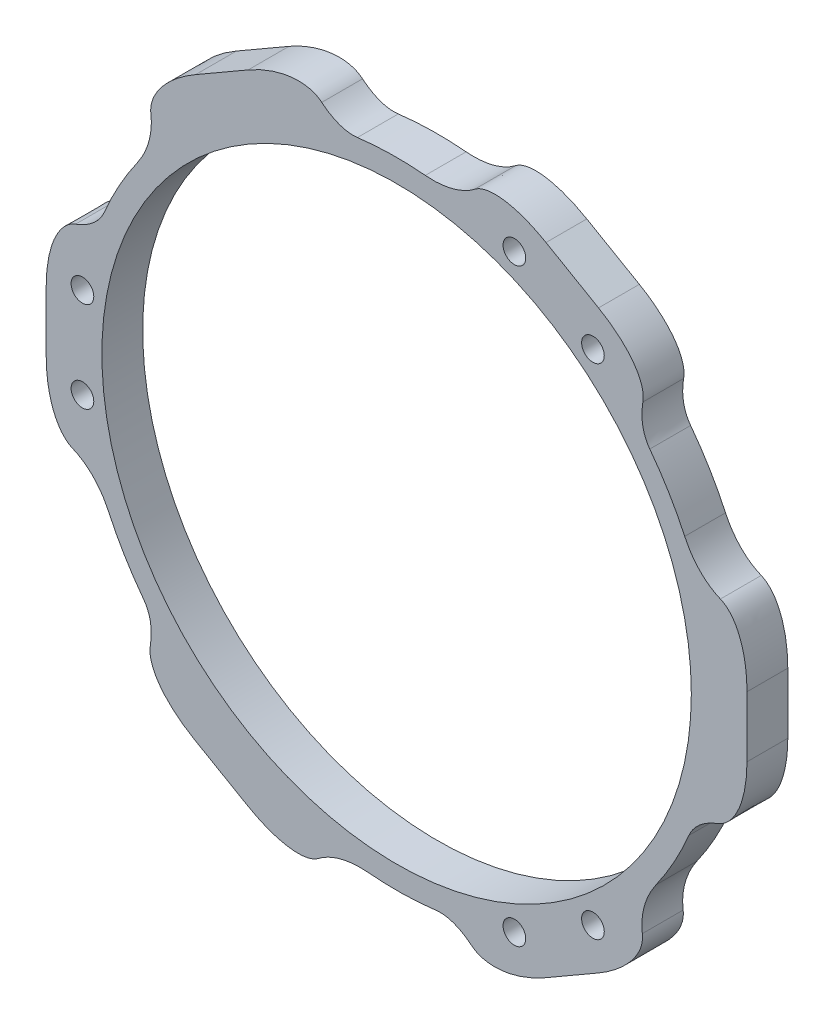
SolidWorks part; units mm, degrees
ref_plane "Front Plane" through (0, 0, 0) normal (0, 0, 1) x (1, 0, 0)
ref_plane "Top Plane" through (0, 0, 0) normal (0, 1, 0) x (1, 0, 0)
ref_plane "Right Plane" through (0, 0, 0) normal (1, 0, 0) x (0, 0, -1)
sketch "Sketch1" plane through (0, 0, 0) normal (0, 0, 1) x (1, 0, 0)
  line L6 (-16.3681, 35.1641) -> (-22.1631, 31.8183)
  line L7 (-38.637, 3.4069) -> (-38.637, -3.2847)
  line L8 (-20.8216, -32.5928) -> (-16.4739, -35.103)
  line L9 (16.3681, -35.1641) -> (22.1631, -31.8183)
  line L10 (38.637, -3.4069) -> (38.637, 3.2847)
  line L11 (22.269, 31.7572) -> (16.4739, 35.103)
  line L12 (-16.3681, 35.1641) -> (-22.1631, 31.8183)
  line L13 (-38.637, 3.4069) -> (-38.637, -3.2847)
  line L15 (16.3681, -35.1641) -> (22.1631, -31.8183)
  line L16 (38.637, -3.4069) -> (38.637, 3.2847)
  line L17 (22.269, 31.7572) -> (16.4739, 35.103)
  line L27 (-16.4739, -35.103) -> (-22.269, -31.7572) construction
  line L28 (-16.4739, -35.103) -> (-22.269, -31.7572)
  line L35 (-27.0644, -24.4754) -> (-24.4721, -21.3861)
  line L37 (-16.8117, -27.814) -> (-20.8216, -32.5928)
  circle A0 centre (-34.641, -5) radius 1.25 construction
  circle A1 centre (-34.641, 5) radius 1.25 construction
  circle A2 centre (12.9904, 32.5) radius 1.25 construction
  circle A3 centre (21.6506, 27.5) radius 1.25 construction
  circle A4 centre (21.6506, -27.5) radius 1.25 construction
  circle A5 centre (12.9904, -32.5) radius 1.25 construction
  arc A6 (-28.6051, 20.1681) -> (-32.2382, 13.6271) centre (0, 0) ccw
  arc A7 (-31.7686, -14.6887) -> (-27.9205, -21.1055) centre (0, 0) ccw
  arc A8 (-3.1635, -34.8567) -> (4.3177, -34.7327) centre (0, 0) ccw
  arc A9 (28.6051, -20.1681) -> (32.2382, -13.6271) centre (0, 0) ccw
  arc A10 (31.7686, 14.6887) -> (27.9205, 21.1055) centre (0, 0) ccw
  arc A11 (3.1635, 34.8567) -> (-4.3177, 34.7327) centre (0, 0) ccw
  arc A12 (-28.6051, 20.1681) -> (-32.2382, 13.6271) centre (0, 0) ccw
  arc A13 (-31.7686, -14.6887) -> (-27.9205, -21.1055) centre (0, 0) ccw
  arc A14 (-3.1635, -34.8567) -> (4.3177, -34.7327) centre (0, 0) ccw
  arc A15 (28.6051, -20.1681) -> (32.2382, -13.6271) centre (0, 0) ccw
  arc A16 (31.7686, 14.6887) -> (27.9205, 21.1055) centre (0, 0) ccw
  arc A17 (3.1635, 34.8567) -> (-4.3177, 34.7327) centre (0, 0) ccw
  circle A18 centre (-34.641, -5) radius 1.25
  circle A19 centre (-34.641, 5) radius 1.25
  circle A20 centre (12.9904, 32.5) radius 1.25
  circle A21 centre (21.6506, 27.5) radius 1.25
  circle A22 centre (21.6506, -27.5) radius 1.25
  circle A23 centre (12.9904, -32.5) radius 1.25
  circle A31 centre (0, 0) radius 32.5
  arc A51 (-16.8117, -27.814) -> (-24.4721, -21.3861) centre (0, 0) ccw
  arc A52 (-16.8117, -27.814) -> (-24.4721, -21.3861) centre (0, 0) ccw construction
  spline S24 degree 2 poles (20018.0304, -6218.9304) (192.3658, 262.0734) (-25.4386, 29.292) (-26.2323, 28.4437) (-26.6615, 27.603) (-123.8009, -162.6744) (20488.8575, 4480.5029) knots -83.757765 -83.757765 -83.757765 0.5 0.5 0.75 0.75 44.47631 44.47631 44.47631 only from (-22.1631, 31.8183) to (-27.0953, 25.5852)
  spline S25 degree 2 poles (-20068.3462, -6225.9324) (-4.2818, 286.6928) (-27.07, 24.2022) (-27.162, 23.1427) (-27.5729, 22.0839) (-136.5452, -258.6621) (-19878.5198, 6847.5241) knots -56.599758 -56.599758 -56.599758 0.5 0.5 0.75 0.75 70.569418 70.569418 70.569418 only from (-27.0953, 25.5852) to (-28.6051, 20.1681)
  spline S26 degree 2 poles (-19304.6139, 8338.2187) (134.0795, 161.3494) (-33.3539, 12.1077) (-34.0252, 11.5093) (-34.9497, 11.0979) (-285.6142, -100.4617) (-13434.0765, 16171.4862) knots -54.854338 -54.854338 -54.854338 0.25 0.25 0.5 0.5 76.100885 76.100885 76.100885 only from (-32.2382, 13.6271) to (-35.408, 10.9116)
  spline S27 degree 2 poles (6375.7637, -19980.6764) (89.3915, 185.5734) (-37.0555, 9.5638) (-37.6258, 8.77) (-38.0064, 7.642) (-38.3307, 6.6806) (-38.491, 5.5483) (-90.1333, -359.2843) (18121.9616, -10520.9097) knots -43.471704 -43.471704 -43.471704 0.25 0.25 0.5 0.5 0.75 0.75 89.168933 89.168933 89.168933 only from (-35.408, 10.9116) to (-38.637, 3.4069)
  spline S28 degree 2 poles (15394.7669, 14226.6576) (-130.7794, 297.6304) (-38.0869, -7.3845) (-37.7491, -8.496) (-37.2357, -9.288) (78.9797, -188.5519) (6364.1994, 19984.1225) knots -83.757765 -83.757765 -83.757765 0.5 0.5 0.75 0.75 44.47631 44.47631 44.47631 only from (-38.637, -3.2847) to (-35.7051, -10.6726)
  spline S29 degree 2 poles (-4642.3575, -20492.6638) (-250.4242, 139.6382) (-34.4947, -11.3422) (-33.6232, -11.9516) (-32.9117, -12.8369) (155.7354, -247.5826) (-15869.3897, -13791.5411) knots -56.599758 -56.599758 -56.599758 0.5 0.5 0.75 0.75 70.569418 70.569418 70.569418 only from (-35.7051, -10.6726) to (-31.7686, -14.6887)
  spline S30 degree 2 poles (-869.2724, -561.5927) (-37.2473, 25.8119) (-27.1625, -22.8314) (-16.9987, -71.8561) (-900.9243, -510.6357) knots -11.954832 -11.954832 -11.954832 0.25 0.25 14.167884 14.167884 14.167884 only from (-27.9205, -21.1055) to (-27.0644, -24.4754)
  spline S31 degree 2 poles (-19740.8402, -3354.4279) (-55.5598, -291.2204) (-27.0871, -24.7299) (-26.9793, -23.7208) (-27.1613, -22.8376) (-71.3618, 191.6829) (-16081.7661, -11939.2208) knots -73.205513 -73.205513 -73.205513 0.5 0.5 0.75 0.75 54.368798 54.368798 54.368798 only from (-27.1537, -25.2085) to (-27.9205, -21.1055) construction
  spline S32 degree 2 poles (-4623.2634, 20445.5881) (-323.1452, 35.5569) (-12.6483, -36.6765) (-11.5168, -36.9397) (-10.5741, -36.891) (202.7806, -25.8775) (-14124.6581, 15503.6196) knots -83.757765 -83.757765 -83.757765 0.5 0.5 0.75 0.75 44.47631 44.47631 44.47631 only from (-16.4739, -35.103) to (-8.6098, -36.2578)
  spline S33 degree 2 poles (15425.9887, -14266.7314) (-246.1423, -147.0546) (-7.4247, -35.5444) (-6.4612, -35.0943) (-5.3387, -34.9208) (292.2805, 11.0795) (4009.1301, -20639.0652) knots -56.599758 -56.599758 -56.599758 0.5 0.5 0.75 0.75 70.569418 70.569418 70.569418 only from (-8.6098, -36.2578) to (-3.1635, -34.8567)
  spline S34 degree 2 poles (2431.1977, -20887.3954) (-206.7724, 35.4415) (6.1913, -34.9392) (7.0452, -35.2214) (7.8638, -35.8163) (229.8095, -197.1183) (-7287.8796, -19719.9947) knots -54.854338 -54.854338 -54.854338 0.25 0.25 0.5 0.5 76.100885 76.100885 76.100885 only from (4.3177, -34.7327) to (8.2543, -36.12)
  spline S35 degree 2 poles (14115.8916, 15511.9115) (-205.407, -15.3714) (10.2452, -36.8729) (11.2179, -36.9699) (12.3851, -36.7355) (13.3798, -36.5357) (14.4405, -36.1083) (356.216, 101.5844) (50.3943, 20954.5339) knots -43.471704 -43.471704 -43.471704 0.25 0.25 0.5 0.5 0.75 0.75 89.168933 89.168933 89.168933 only from (8.2543, -36.12) to (16.3681, -35.1641)
  spline S36 degree 2 poles (-20018.0304, 6218.9305) (-192.3658, -262.0734) (25.4386, -29.292) (26.2323, -28.4437) (26.6615, -27.603) (123.8009, 162.6744) (-20488.8575, -4480.5029) knots -83.757765 -83.757765 -83.757765 0.5 0.5 0.75 0.75 44.47631 44.47631 44.47631 only from (22.1631, -31.8183) to (27.0953, -25.5852)
  spline S37 degree 2 poles (20068.3462, 6225.9324) (4.2818, -286.6928) (27.07, -24.2022) (27.162, -23.1427) (27.5729, -22.0839) (136.5452, 258.6621) (19878.5198, -6847.5241) knots -56.599758 -56.599758 -56.599758 0.5 0.5 0.75 0.75 70.569418 70.569418 70.569418 only from (27.0953, -25.5852) to (28.6051, -20.1681)
  spline S38 degree 2 poles (19304.6139, -8338.2187) (-134.0795, -161.3494) (33.3539, -12.1077) (34.0252, -11.5093) (34.9497, -11.0979) (285.6142, 100.4617) (13434.0765, -16171.4862) knots -54.854338 -54.854338 -54.854338 0.25 0.25 0.5 0.5 76.100885 76.100885 76.100885 only from (32.2382, -13.6271) to (35.408, -10.9116)
  spline S39 degree 2 poles (-6375.7637, 19980.6764) (-89.3915, -185.5734) (37.0555, -9.5638) (37.6258, -8.77) (38.0064, -7.642) (38.3307, -6.6806) (38.491, -5.5483) (90.1333, 359.2843) (-18121.9616, 10520.9097) knots -43.471704 -43.471704 -43.471704 0.25 0.25 0.5 0.5 0.75 0.75 89.168933 89.168933 89.168933 only from (35.408, -10.9116) to (38.637, -3.4069)
  spline S40 degree 2 poles (-15394.7669, -14226.6576) (130.7794, -297.6304) (38.0869, 7.3845) (37.7491, 8.496) (37.2357, 9.288) (-78.9797, 188.5519) (-6364.1994, -19984.1225) knots -83.757765 -83.757765 -83.757765 0.5 0.5 0.75 0.75 44.47631 44.47631 44.47631 only from (38.637, 3.2847) to (35.7051, 10.6726)
  spline S41 degree 2 poles (4642.3575, 20492.6638) (250.4242, -139.6382) (34.4947, 11.3422) (33.6232, 11.9516) (32.9117, 12.8369) (-155.7354, 247.5826) (15869.3897, 13791.5411) knots -56.599758 -56.599758 -56.599758 0.5 0.5 0.75 0.75 70.569418 70.569418 70.569418 only from (35.7051, 10.6726) to (31.7686, 14.6887)
  spline S42 degree 2 poles (16873.4162, 12549.1767) (72.6929, -196.7909) (27.1625, 22.8314) (26.98, 23.712) (27.0859, 24.7184) (55.8047, 297.58) (20721.9561, 3548.5085) knots -54.854338 -54.854338 -54.854338 0.25 0.25 0.5 0.5 76.100885 76.100885 76.100885 only from (27.9205, 21.1055) to (27.1537, 25.2085)
  spline S43 degree 2 poles (-20491.6552, 4468.7649) (116.0155, -170.202) (26.8103, 27.3091) (26.4079, 28.1999) (25.6213, 29.0935) (24.951, 29.8551) (24.0505, 30.56) (-266.0827, 257.6999) (-18172.3559, -10433.6242) knots -43.471704 -43.471704 -43.471704 0.25 0.25 0.5 0.5 0.75 0.75 89.168933 89.168933 89.168933 only from (27.1537, 25.2085) to (22.269, 31.7572)
  spline S44 degree 2 poles (4623.2634, -20445.5881) (323.1452, -35.5569) (12.6483, 36.6765) (11.5168, 36.9397) (10.5741, 36.891) (-202.7806, 25.8775) (14124.6581, -15503.6196) knots -83.757765 -83.757765 -83.757765 0.5 0.5 0.75 0.75 44.47631 44.47631 44.47631 only from (16.4739, 35.103) to (8.6098, 36.2578)
  spline S45 degree 2 poles (-15425.9887, 14266.7314) (246.1423, 147.0546) (7.4247, 35.5444) (6.4612, 35.0943) (5.3387, 34.9208) (-292.2805, -11.0795) (-4009.1301, 20639.0652) knots -56.599758 -56.599758 -56.599758 0.5 0.5 0.75 0.75 70.569418 70.569418 70.569418 only from (8.6098, 36.2578) to (3.1635, 34.8567)
  spline S46 degree 2 poles (-2431.1977, 20887.3954) (206.7724, -35.4415) (-6.1913, 34.9392) (-7.0452, 35.2214) (-7.8638, 35.8163) (-229.8095, 197.1183) (7287.8796, 19719.9947) knots -54.854338 -54.854338 -54.854338 0.25 0.25 0.5 0.5 76.100885 76.100885 76.100885 only from (-4.3177, 34.7327) to (-8.2543, 36.12)
  spline S47 degree 2 poles (-14115.8916, -15511.9115) (205.407, 15.3714) (-10.2452, 36.8729) (-11.2179, 36.9699) (-12.3851, 36.7355) (-13.3798, 36.5357) (-14.4405, 36.1083) (-356.216, -101.5844) (-50.3943, -20954.5339) knots -43.471704 -43.471704 -43.471704 0.25 0.25 0.5 0.5 0.75 0.75 89.168933 89.168933 89.168933 only from (-8.2543, 36.12) to (-16.3681, 35.1641)
  spline S48 degree 2 poles (-22.1631, 31.8183) (-24.1461, 30.6734) (-25.4386, 29.292) (-26.2323, 28.4437) (-26.6615, 27.603) (-27.2169, 26.5151) (-27.0953, 25.5852) knots 0 0 0 0.5 0.5 0.75 0.75 1 1 1
  spline S49 degree 2 poles (-27.0953, 25.5852) (-27.0077, 24.919) (-27.07, 24.2022) (-27.162, 23.1427) (-27.5729, 22.0839) (-27.9631, 21.0786) (-28.6051, 20.1681) knots 0.344078 0.344078 0.344078 0.5 0.5 0.75 0.75 1 1 1
  spline S50 degree 2 poles (-32.2382, 13.6271) (-32.5943, 12.7848) (-33.3539, 12.1077) (-34.0252, 11.5093) (-34.9497, 11.0979) (-35.1737, 10.9982) (-35.408, 10.9116) knots 0 0 0 0.25 0.25 0.5 0.5 0.567561 0.567561 0.567561
  spline S51 degree 2 poles (-35.408, 10.9116) (-36.3325, 10.5702) (-37.0555, 9.5638) (-37.6258, 8.77) (-38.0064, 7.642) (-38.3307, 6.6806) (-38.491, 5.5483) (-38.637, 4.5167) (-38.637, 3.4069) knots 0 0 0 0.25 0.25 0.5 0.5 0.75 0.75 1 1 1
  spline S52 degree 2 poles (-38.637, -3.2847) (-38.637, -5.5744) (-38.0869, -7.3845) (-37.7491, -8.496) (-37.2357, -9.288) (-36.5712, -10.313) (-35.7051, -10.6726) knots 0 0 0 0.5 0.5 0.75 0.75 1 1 1
  spline S53 degree 2 poles (-35.7051, -10.6726) (-35.0843, -10.9299) (-34.4947, -11.3422) (-33.6232, -11.9516) (-32.9117, -12.8369) (-32.2362, -13.6775) (-31.7686, -14.6887) knots 0.344078 0.344078 0.344078 0.5 0.5 0.75 0.75 1 1 1
  spline S54 degree 2 poles (17259.9062, 10015.0737) (259.5076, -252.7064) (-24.0549, -30.5565) (-24.9503, -29.8551) (-25.619, -29.0962) (-26.4039, -28.2053) (-26.8075, -27.3152) (-114.209, 165.455) (19522.6916, -4218.626) knots -85.924255 -85.924255 -85.924255 0.25 0.25 0.5 0.5 0.75 0.75 43.310793 43.310793 43.310793 only from (-22.269, -31.7572) to (-27.1537, -25.2085) construction
  spline S55 degree 2 poles (-27.1537, -25.2085) (-27.1126, -24.9681) (-27.0871, -24.7299) (-26.9793, -23.7208) (-27.1613, -22.8376) (-27.3674, -21.8374) (-27.9205, -21.1055) knots 0.434124 0.434124 0.434124 0.5 0.5 0.75 0.75 1 1 1
  spline S56 degree 2 poles (-16.4739, -35.103) (-14.4909, -36.2478) (-12.6483, -36.6765) (-11.5168, -36.9397) (-10.5741, -36.891) (-9.3543, -36.8281) (-8.6098, -36.2578) knots 0 0 0 0.5 0.5 0.75 0.75 1 1 1
  spline S57 degree 2 poles (-8.6098, -36.2578) (-8.0766, -35.8489) (-7.4247, -35.5444) (-6.4612, -35.0943) (-5.3387, -34.9208) (-4.273, -34.7561) (-3.1635, -34.8567) knots 0.344078 0.344078 0.344078 0.5 0.5 0.75 0.75 1 1 1
  spline S58 degree 2 poles (4.3177, -34.7327) (5.2252, -34.6199) (6.1913, -34.9392) (7.0452, -35.2214) (7.8638, -35.8163) (8.0622, -35.9604) (8.2543, -36.12) knots 0 0 0 0.25 0.25 0.5 0.5 0.567561 0.567561 0.567561
  spline S59 degree 2 poles (8.2543, -36.12) (9.0121, -36.75) (10.2452, -36.8729) (11.2179, -36.9699) (12.3851, -36.7355) (13.3798, -36.5357) (14.4405, -36.1083) (15.4069, -35.719) (16.3681, -35.1641) knots 0 0 0 0.25 0.25 0.5 0.5 0.75 0.75 1 1 1
  spline S60 degree 2 poles (22.1631, -31.8183) (24.1461, -30.6734) (25.4386, -29.292) (26.2323, -28.4437) (26.6615, -27.603) (27.2169, -26.5151) (27.0953, -25.5852) knots 0 0 0 0.5 0.5 0.75 0.75 1 1 1
  spline S61 degree 2 poles (27.0953, -25.5852) (27.0077, -24.919) (27.07, -24.2022) (27.162, -23.1427) (27.5729, -22.0839) (27.9631, -21.0786) (28.6051, -20.1681) knots 0.344078 0.344078 0.344078 0.5 0.5 0.75 0.75 1 1 1
  spline S62 degree 2 poles (32.2382, -13.6271) (32.5943, -12.7848) (33.3539, -12.1077) (34.0252, -11.5093) (34.9497, -11.0979) (35.1737, -10.9982) (35.408, -10.9116) knots 0 0 0 0.25 0.25 0.5 0.5 0.567561 0.567561 0.567561
  spline S63 degree 2 poles (35.408, -10.9116) (36.3325, -10.5702) (37.0555, -9.5638) (37.6258, -8.77) (38.0064, -7.642) (38.3307, -6.6806) (38.491, -5.5483) (38.637, -4.5167) (38.637, -3.4069) knots 0 0 0 0.25 0.25 0.5 0.5 0.75 0.75 1 1 1
  spline S64 degree 2 poles (38.637, 3.2847) (38.637, 5.5744) (38.0869, 7.3845) (37.7491, 8.496) (37.2357, 9.288) (36.5712, 10.313) (35.7051, 10.6726) knots 0 0 0 0.5 0.5 0.75 0.75 1 1 1
  spline S65 degree 2 poles (35.7051, 10.6726) (35.0843, 10.9299) (34.4947, 11.3422) (33.6232, 11.9516) (32.9117, 12.8369) (32.2362, 13.6775) (31.7686, 14.6887) knots 0.344078 0.344078 0.344078 0.5 0.5 0.75 0.75 1 1 1
  spline S66 degree 2 poles (27.9205, 21.1055) (27.3691, 21.835) (27.1625, 22.8314) (26.98, 23.712) (27.0859, 24.7184) (27.1116, 24.9622) (27.1537, 25.2085) knots 0 0 0 0.25 0.25 0.5 0.5 0.567561 0.567561 0.567561
  spline S67 degree 2 poles (27.1537, 25.2085) (27.3203, 26.1797) (26.8103, 27.3091) (26.4079, 28.1999) (25.6213, 29.0935) (24.951, 29.8551) (24.0505, 30.56) (23.2301, 31.2023) (22.269, 31.7572) knots 0 0 0 0.25 0.25 0.5 0.5 0.75 0.75 1 1 1
  spline S68 degree 2 poles (16.4739, 35.103) (14.4909, 36.2478) (12.6483, 36.6765) (11.5168, 36.9397) (10.5741, 36.891) (9.3543, 36.8281) (8.6098, 36.2578) knots 0 0 0 0.5 0.5 0.75 0.75 1 1 1
  spline S69 degree 2 poles (8.6098, 36.2578) (8.0766, 35.8489) (7.4247, 35.5444) (6.4612, 35.0943) (5.3387, 34.9208) (4.273, 34.7561) (3.1635, 34.8567) knots 0.344078 0.344078 0.344078 0.5 0.5 0.75 0.75 1 1 1
  spline S70 degree 2 poles (-4.3177, 34.7327) (-5.2252, 34.6199) (-6.1913, 34.9392) (-7.0452, 35.2214) (-7.8638, 35.8163) (-8.0622, 35.9604) (-8.2543, 36.12) knots 0 0 0 0.25 0.25 0.5 0.5 0.567561 0.567561 0.567561
  spline S71 degree 2 poles (-8.2543, 36.12) (-9.0121, 36.75) (-10.2452, 36.8729) (-11.2179, 36.9699) (-12.3851, 36.7355) (-13.3798, 36.5357) (-14.4405, 36.1083) (-15.4069, 35.719) (-16.3681, 35.1641) knots 0 0 0 0.25 0.25 0.5 0.5 0.75 0.75 1 1 1
  spline S99 degree 2 poles (-22.269, -31.7572) (-23.2323, -31.201) (-24.0549, -30.5565) (-24.9503, -29.8551) (-25.619, -29.0962) (-26.4039, -28.2053) (-26.8075, -27.3152) (-27.3209, -26.1829) (-27.1537, -25.2085) knots 0 0 0 0.25 0.25 0.5 0.5 0.75 0.75 1 1 1
  point P69 (0, 0)
  dimension "D1" = 0
extrude "Boss-Extrude1" add sketch "Sketch1" along normal blind 4.5
